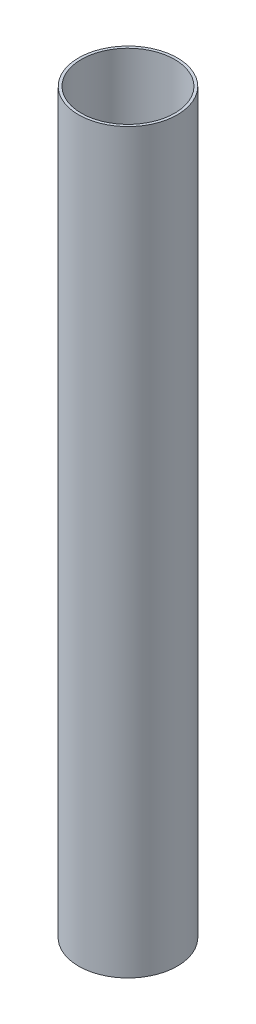
SolidWorks part; units mm, degrees
ref_plane "Front Plane" through (0, 0, 0) normal (0, 0, 1) x (1, 0, 0)
ref_plane "Top Plane" through (0, 0, 0) normal (0, 1, 0) x (1, 0, 0)
ref_plane "Right Plane" through (0, 0, 0) normal (1, 0, 0) x (0, 0, -1)
sketch "Sketch1" plane through (0, 0, 0) normal (0, 1, 0) x (1, 0, 0)
  circle A0 centre (0, 0) radius 28.9052
  circle A1 centre (0, 0) radius 27.3304
  dimension "D1" = 54.6608
  dimension "D2" = 57.8104
extrude "Boss-Extrude1" add sketch "Sketch1" along normal blind 431.8
